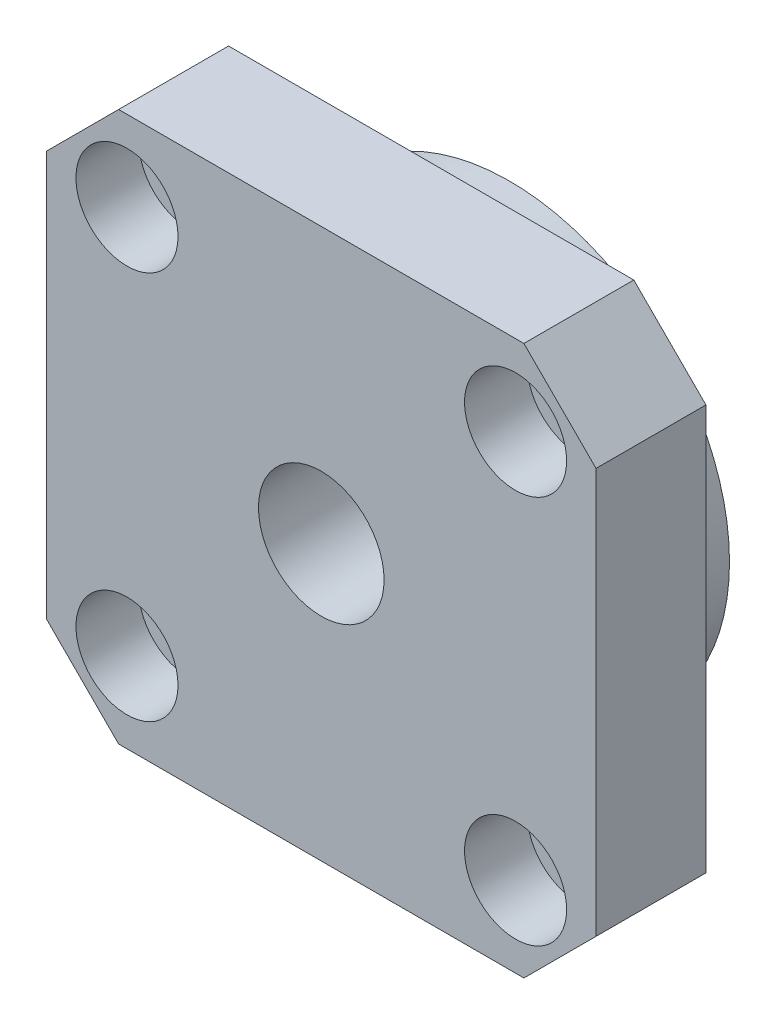
SolidWorks part; units mm, degrees
material "AISI 304"
ref_plane "前视基准面" through (0, 0, 0) normal (0, 0, 1) x (1, 0, 0)
ref_plane "上视基准面" through (0, 0, 0) normal (0, 1, 0) x (1, 0, 0)
ref_plane "右视基准面" through (0, 0, 0) normal (1, 0, 0) x (0, 0, -1)
other "Configuration Table"
sketch "草图1" plane through (0, 0, 0) normal (0, 0, 1) x (1, 0, 0)
  circle A0 centre (0, 0) radius 14
  circle A1 centre (0, 0) radius 4
  dimension "D1" = 8
  dimension "D2" = 28
extrude "凸台-拉伸1" add sketch "草图1" along normal blind 5
sketch "草图2" plane through (0, 0, 5) normal (0, 0, 1) x (1, 0, 0)
  line L0 (-17.5, 12.9056) -> (-12.9056, 17.5)
  line L1 (-12.9056, 17.5) -> (12.9056, 17.5)
  line L2 (-17.5, 12.9056) -> (-17.5, -12.9056)
  line L3 (-12.9056, -17.5) -> (12.9056, -17.5)
  line L4 (17.5, 12.9056) -> (17.5, -12.9056)
  line L5 (-17.5, 17.5) -> (17.5, -17.5) construction
  line L6 (-17.5, -17.5) -> (17.5, 17.5) construction
  line L7 (12.9056, 17.5) -> (17.5, 12.9056)
  line L10 (-17.5, -12.9056) -> (-12.9056, -17.5)
  line L11 (12.9056, -17.5) -> (17.5, -12.9056)
  circle A0 centre (0, 0) radius 4
  circle A1 centre (0, 0) radius 17.5 construction
  circle A2 centre (-12.3744, 12.3744) radius 1.7
  circle A4 centre (12.3744, 12.3744) radius 1.7
  circle A5 centre (12.3744, -12.3744) radius 1.7
  circle A6 centre (-12.3744, -12.3744) radius 1.7
  point P19 (0, 0)
  dimension "D1" = 8
  dimension "D2" = 43
  dimension "D6" = 3.4
  dimension "D3" = 35
  dimension "D4" = 35
  dimension "D5" = 4
extrude "凸台-拉伸2" add sketch "草图2" along normal blind 7
sketch "草图3" plane through (0, 0, 12) normal (0, 0, 1) x (1, 0, 0)
  circle A0 centre (-12.3744, 12.3744) radius 3.25
  circle A1 centre (12.3744, 12.3744) radius 3.25
  circle A2 centre (12.3744, -12.3744) radius 3.25
  circle A3 centre (-12.3744, -12.3744) radius 3.25
  point P12 (0, 0)
  dimension "D2" = 6.5
  dimension "D1" = 4
extrude "切除-拉伸1" cut sketch "草图3" against normal blind 4
sketch "草图4" plane through (0, 0, 0) normal (0, 0, -1) x (-1, 0, 0)
  circle A0 centre (0, 0) radius 10
  dimension "D1" = 20
extrude "切除-拉伸2" cut sketch "草图4" against normal blind 5
